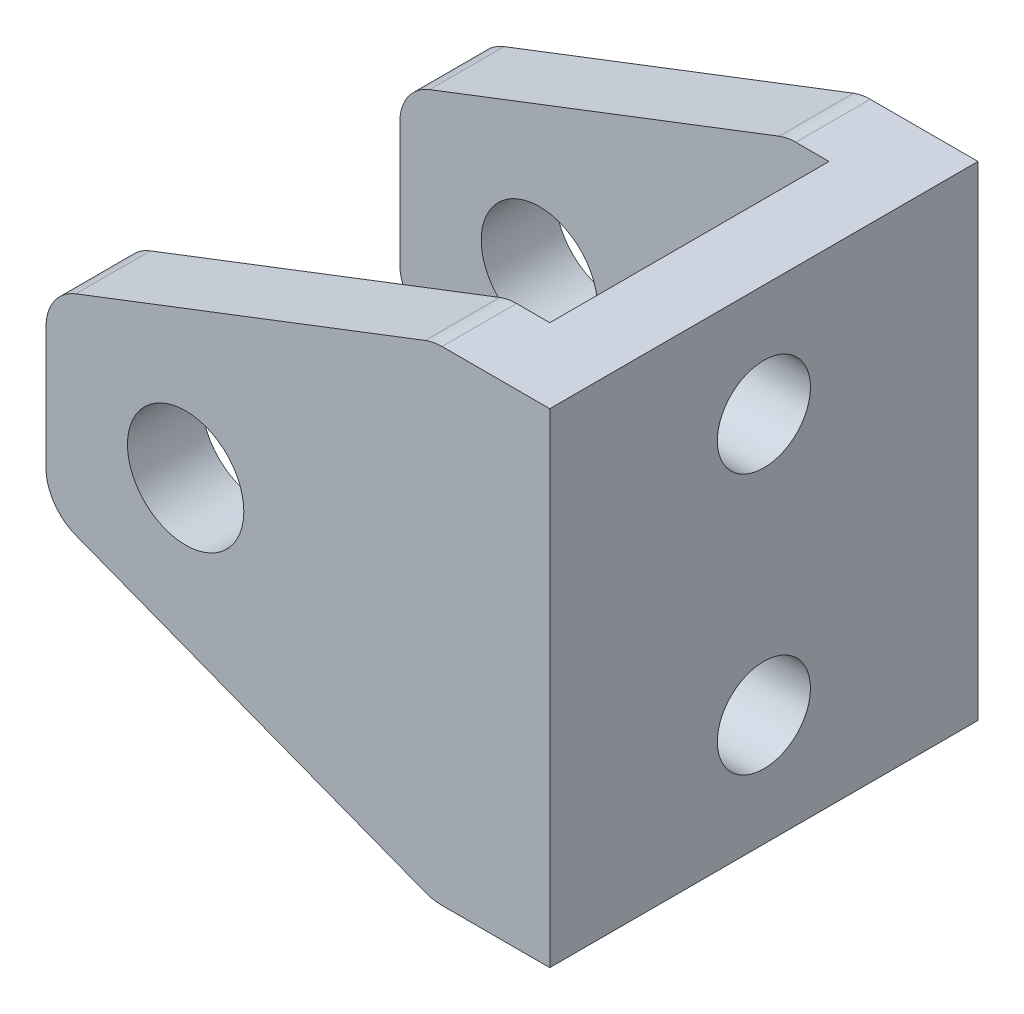
SolidWorks part; units mm, degrees
ref_plane "Front Plane" through (0, 0, 0) normal (0, 0, 1) x (1, 0, 0)
ref_plane "Top Plane" through (0, 0, 0) normal (0, 1, 0) x (1, 0, 0)
ref_plane "Right Plane" through (0, 0, 0) normal (1, 0, 0) x (0, 0, -1)
sketch "Sketch1" plane through (0, -759.0521, 0) normal (0, -1, 0) x (-1, 0, 0)
  line L11 (0, 14.605) -> (0, -14.605)
  line L12 (0, 14.605) -> (34.3616, 14.605)
  line L13 (34.3616, 14.605) -> (34.3616, 9.525)
  line L16 (34.3616, 9.525) -> (5.08, 9.525)
  line L17 (5.08, 9.525) -> (5.08, -9.525)
  line L18 (5.08, -9.525) -> (34.3616, -9.525)
  line L19 (34.3616, -9.525) -> (34.3616, -14.605)
  line L20 (34.3616, -14.605) -> (0, -14.605)
  line L21 (24.8366, 14.605) -> (24.8366, -14.605) construction
  point P3 (0, 0)
  dimension "D1" = 5.08
  dimension "D2" = 5.08
  dimension "D3" = 5.08
  dimension "D4" = 24.8366
  dimension "D5" = 9.525
  dimension "D6" = 19.05
extrude "Boss-Extrude1" add sketch "Sketch1" along normal blind 33.02 contours L13 L16 L17 L18 L19 L20 L11 L12
sketch "Sketch2" plane through (0, 0, 0) normal (1, 0, 0) x (0, 0, -1)
  line L0 (0, -792.0721) -> (0, -759.0521) construction
  line L1 (14.605, -792.0721) -> (-14.605, -792.0721) construction
  line L2 (14.605, -759.0521) -> (-14.605, -759.0521) construction
  circle A0 centre (0, -784.4521) radius 3.175
  circle A1 centre (0, -766.6721) radius 3.175
  dimension "D1" = 6.35
  dimension "D2" = 7.62
  dimension "D3" = 7.62
extrude "Cut-Extrude1" cut sketch "Sketch2" against normal up to next
sketch "Sketch3" plane through (0, 0, 14.605) normal (0, 0, 1) x (1, 0, 0)
  line L0 (0, -792.0721) -> (0, -759.0521) construction
  line L1 (-7.9375, -759.0521) -> (-34.3616, -769.2121)
  line L2 (-34.3616, -759.0521) -> (0, -759.0521) construction
  line L3 (-34.3616, -769.2121) -> (-34.3616, -759.0521)
  line L4 (-34.3616, -759.0521) -> (-7.9375, -759.0521)
  line L5 (-34.3616, -792.0721) -> (-34.3616, -781.9121)
  line L6 (-34.3616, -792.0721) -> (-34.3616, -759.0521) construction
  line L7 (-34.3616, -781.9121) -> (-7.9375, -792.0721)
  line L8 (-34.3616, -792.0721) -> (0, -792.0721) construction
  line L9 (-7.9375, -792.0721) -> (-34.3616, -792.0721)
  circle A0 centre (-24.8366, -775.5621) radius 3.9687
  point P5 (0, -775.5621)
  dimension "D2" = 7.9375
  dimension "D1" = 24.8366
  dimension "D3" = 7.9375
  dimension "D4" = 10.16
extrude "Cut-Extrude2" cut sketch "Sketch3" against normal through all
fillet "Fillet1" radius 3.175 8 edges at (-7.9375, -759.0521, -12.065) (-7.9375, -759.0521, 12.065) (-7.9375, -792.0721, 12.065) (-7.9375, -792.0721, -12.065) (-34.3616, -781.9121, -12.065) (-34.3616, -769.2121, -12.065) (-34.3616, -769.2121, 12.065) (-34.3616, -781.9121, 12.065)
